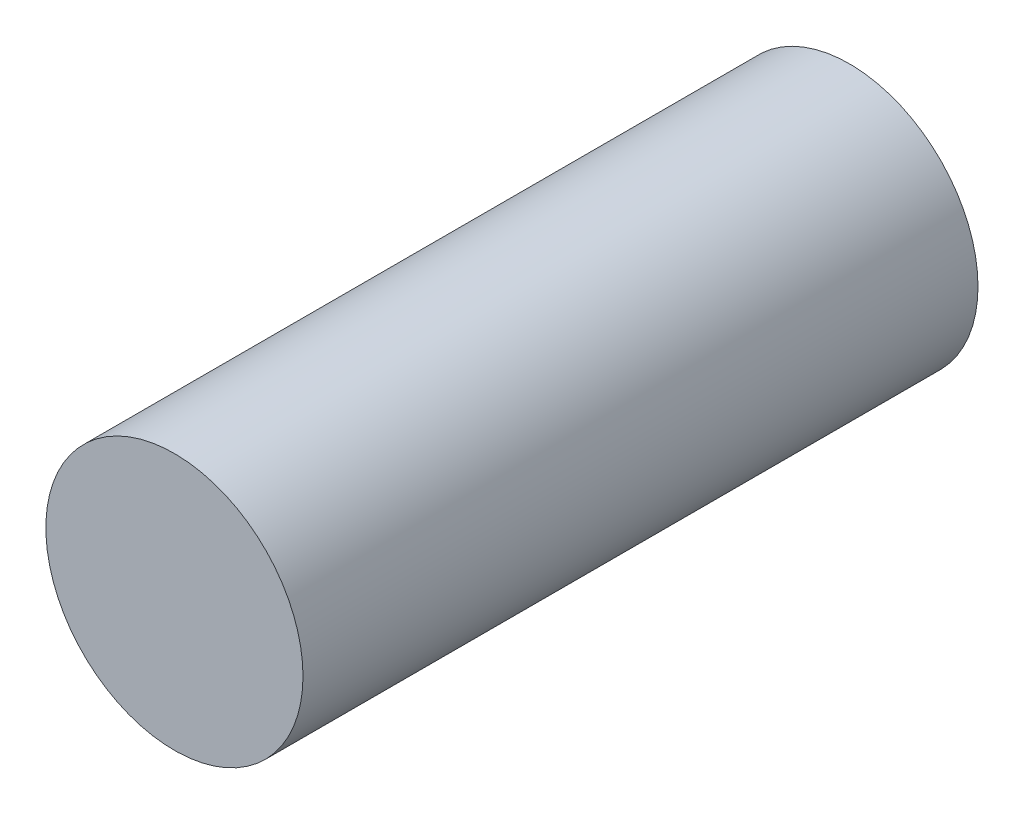
SolidWorks part; units mm, degrees
ref_plane "Front Plane" through (0, 0, 0) normal (0, 0, 1) x (1, 0, 0)
ref_plane "Top Plane" through (0, 0, 0) normal (0, 1, 0) x (1, 0, 0)
ref_plane "Right Plane" through (0, 0, 0) normal (1, 0, 0) x (0, 0, -1)
sketch "Sketch1" plane through (0, 0, 0) normal (0, 0, 1) x (1, 0, 0)
  circle A0 centre (0, 0) radius 40
  dimension "D1" = 80
extrude "Boss-Extrude1" add sketch "Sketch1" along normal blind 210
sketch "Sketch2" plane through (0, 0, 0) normal (0, 0, -1) x (-1, 0, 0)
  point P0 (0, 0)
ref_plane "Plane1" through (0, 0, 105) normal (0, 0, -1) x (-1, 0, 0)
sketch "Sketch3" plane through (0, 0, 105) normal (0, 0, -1) x (-1, 0, 0)
  point P0 (0, 0)
